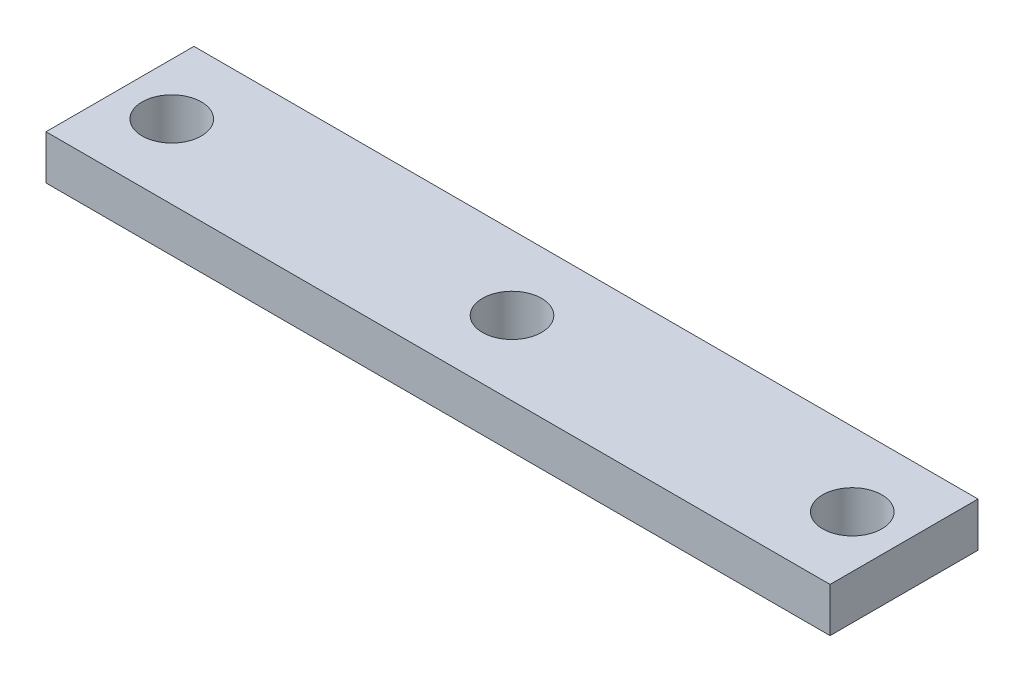
SolidWorks part; units mm, degrees
ref_plane "Front Plane" through (0, 0, 0) normal (0, 0, 1) x (1, 0, 0)
ref_plane "Top Plane" through (0, 0, 0) normal (0, 1, 0) x (1, 0, 0)
ref_plane "Right Plane" through (0, 0, 0) normal (1, 0, 0) x (0, 0, -1)
sketch "Sketch1" plane through (0, 0, 0) normal (0, 1, 0) x (1, 0, 0)
  line L0 (0, 0) -> (-23, 0) construction
  line L1 (-26.5, -5) -> (26.5, -5)
  line L2 (-26.5, -5) -> (-26.5, 5)
  line L3 (-26.5, 5) -> (26.5, 5)
  line L4 (26.5, -5) -> (26.5, 5)
  line L5 (-26.5, -5) -> (26.5, 5) construction
  line L6 (-26.5, 5) -> (26.5, -5) construction
  line L7 (0, 0) -> (23, 0) construction
  circle A0 centre (-23, 0) radius 2
  circle A1 centre (23, 0) radius 2
  circle A2 centre (0, 0) radius 2
  point P0 (0, 0)
  dimension "D4" = 4
  dimension "D1" = 53
  dimension "D2" = 10
  dimension "D3" = 23
extrude "Boss-Extrude1" add sketch "Sketch1" along normal blind 3
